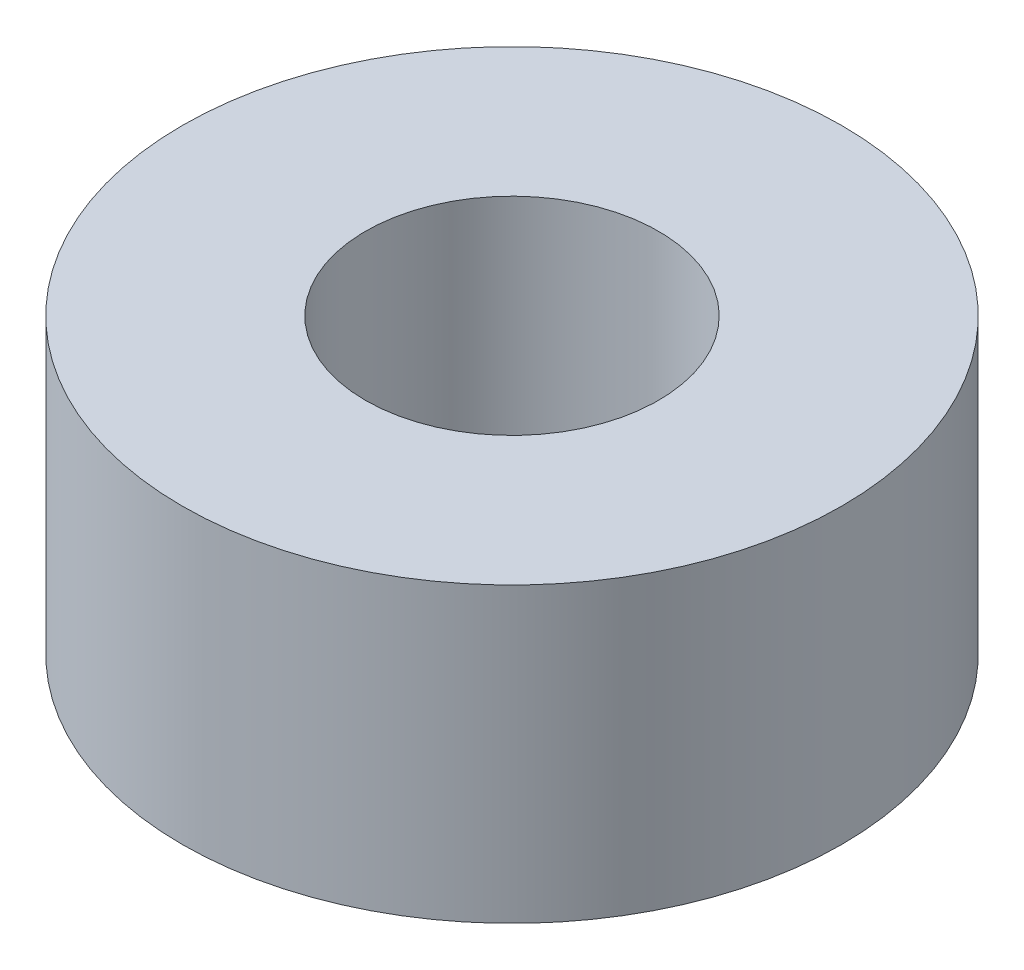
SolidWorks part; units mm, degrees
ref_plane "Front Plane" through (0, 0, 0) normal (0, 0, 1) x (1, 0, 0)
ref_plane "Top Plane" through (0, 0, 0) normal (0, 1, 0) x (1, 0, 0)
ref_plane "Right Plane" through (0, 0, 0) normal (1, 0, 0) x (0, 0, -1)
sketch "Sketch1" plane through (0, 0, 0) normal (0, 1, 0) x (1, 0, 0)
  circle A0 centre (0, 0) radius 4.5
  circle A1 centre (0, 0) radius 2
  dimension "D1" = 4
  dimension "D2" = 9
extrude "Boss-Extrude1" add sketch "Sketch1" along normal blind 4
